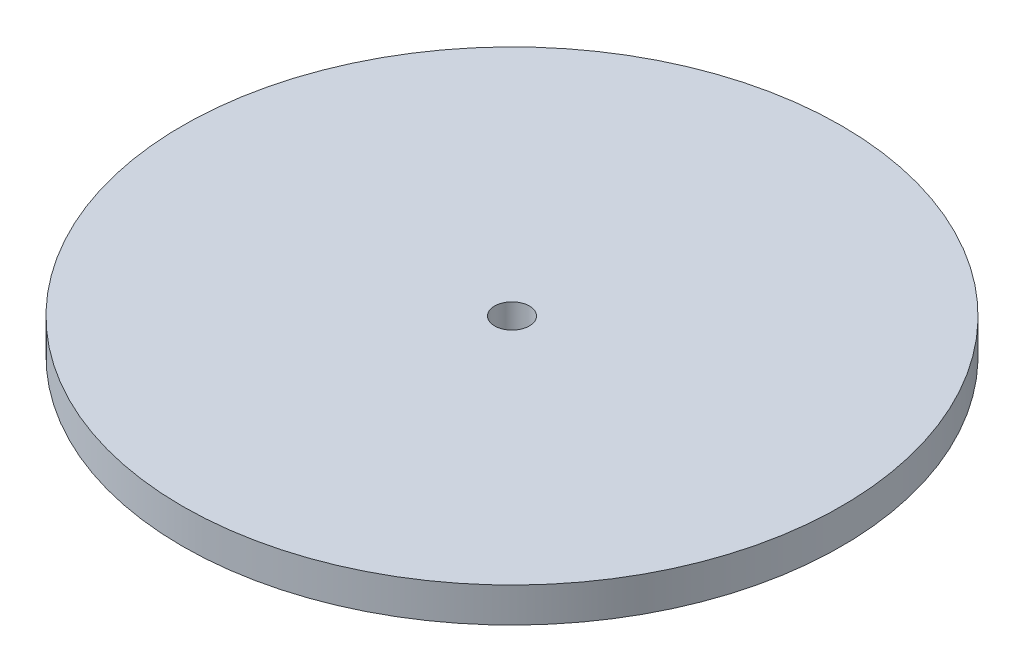
SolidWorks part; units mm, degrees
ref_plane "Front Plane" through (0, 0, 0) normal (0, 0, 1) x (1, 0, 0)
ref_plane "Top Plane" through (0, 0, 0) normal (0, 1, 0) x (1, 0, 0)
ref_plane "Right Plane" through (0, 0, 0) normal (1, 0, 0) x (0, 0, -1)
sketch "Sketch1" plane through (0, 0, 0) normal (0, 1, 0) x (1, 0, 0)
  circle A0 centre (0, 0) radius 19
  dimension "D1" = 38
extrude "Boss-Extrude1" add sketch "Sketch1" along normal blind 2
sketch "Sketch2" plane through (0, 2, 0) normal (0, 1, 0) x (1, 0, 0)
  circle A0 centre (0, 0) radius 1
  dimension "D1" = 2
extrude "Cut-Extrude1" cut sketch "Sketch2" against normal blind 2
